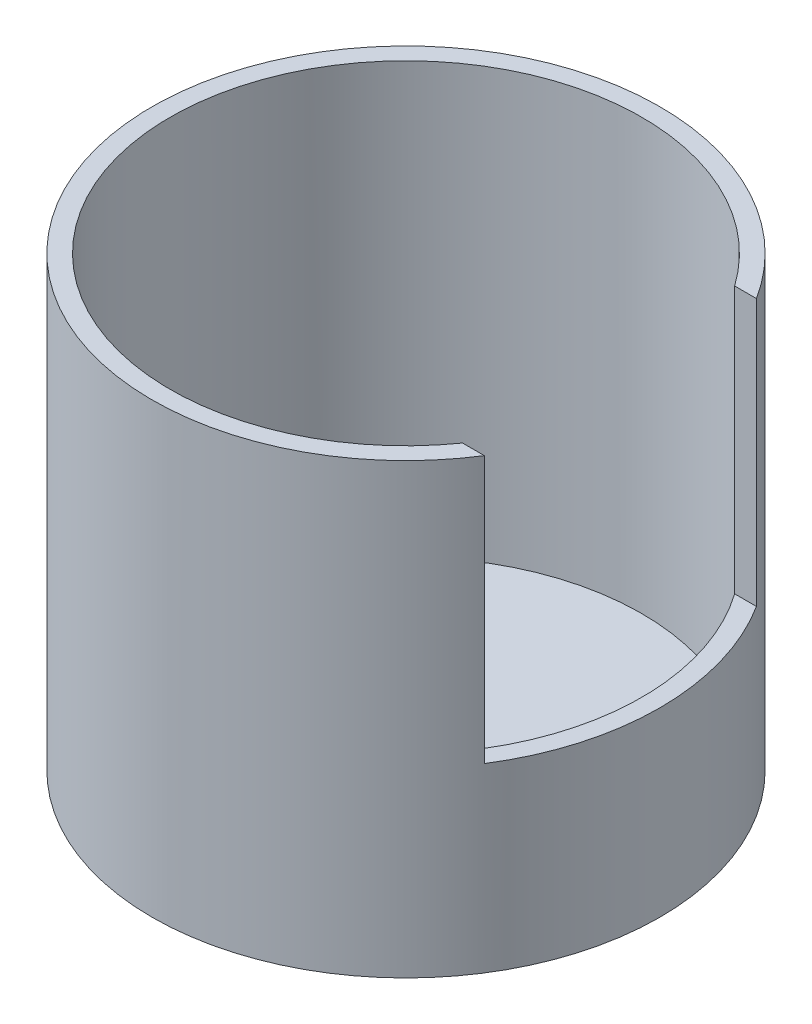
SolidWorks part; units mm, degrees
ref_plane "Front Plane" through (0, 0, 0) normal (0, 0, 1) x (1, 0, 0)
ref_plane "Top Plane" through (0, 0, 0) normal (0, 1, 0) x (1, 0, 0)
ref_plane "Right Plane" through (0, 0, 0) normal (1, 0, 0) x (0, 0, -1)
sketch "Sketch1" plane through (0, 0, 0) normal (0, 1, 0) x (1, 0, 0)
  circle A0 centre (0, 0) radius 14
  dimension "D1" = 28
extrude "Boss-Extrude1" add sketch "Sketch1" along normal blind 24.7
shell "Shell1" thickness 1
sketch "Sketch2" plane through (0, 0, 0) normal (1, 0, 0) x (0, 0, -1)
  line L1 (-7.5, 24.7) -> (7.5, 24.7)
  line L2 (-7.5, 24.7) -> (-7.5, 10)
  line L3 (-7.5, 10) -> (7.5, 10)
  line L4 (7.5, 24.7) -> (7.5, 10)
  dimension "D1" = 15
  dimension "D2" = 14.7
  dimension "D3" = 10
  dimension "D4" = 7.5
extrude "Cut-Extrude1" cut sketch "Sketch2" along normal blind 24.7
